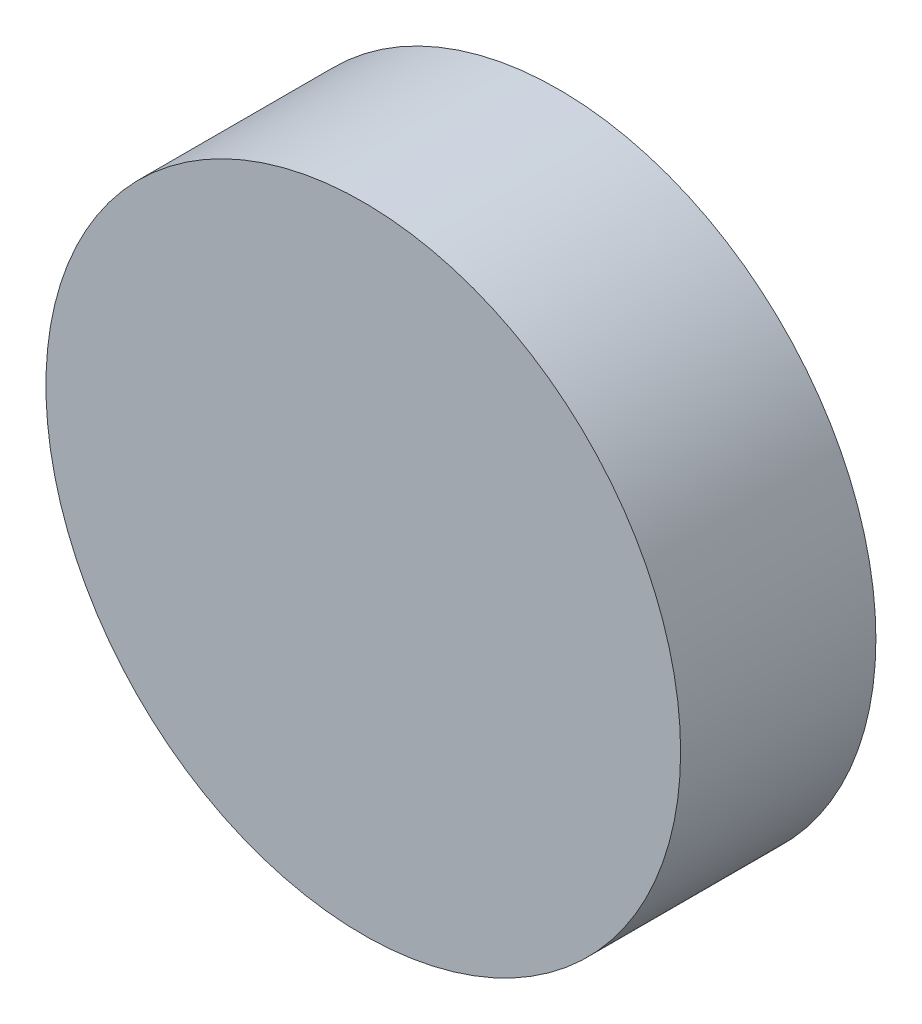
SolidWorks part; units mm, degrees
ref_plane "Front Plane" through (0, 0, 0) normal (0, 0, 1) x (1, 0, 0)
ref_plane "Top Plane" through (0, 0, 0) normal (0, 1, 0) x (1, 0, 0)
ref_plane "Right Plane" through (0, 0, 0) normal (1, 0, 0) x (0, 0, -1)
sketch "Sketch1" plane through (0, 0, 0) normal (0, 0, 1) x (1, 0, 0)
  circle A0 centre (0, 0) radius 8.255
  dimension "D1" = 16.51
extrude "Boss-Extrude1" add sketch "Sketch1" along normal blind 5.08
